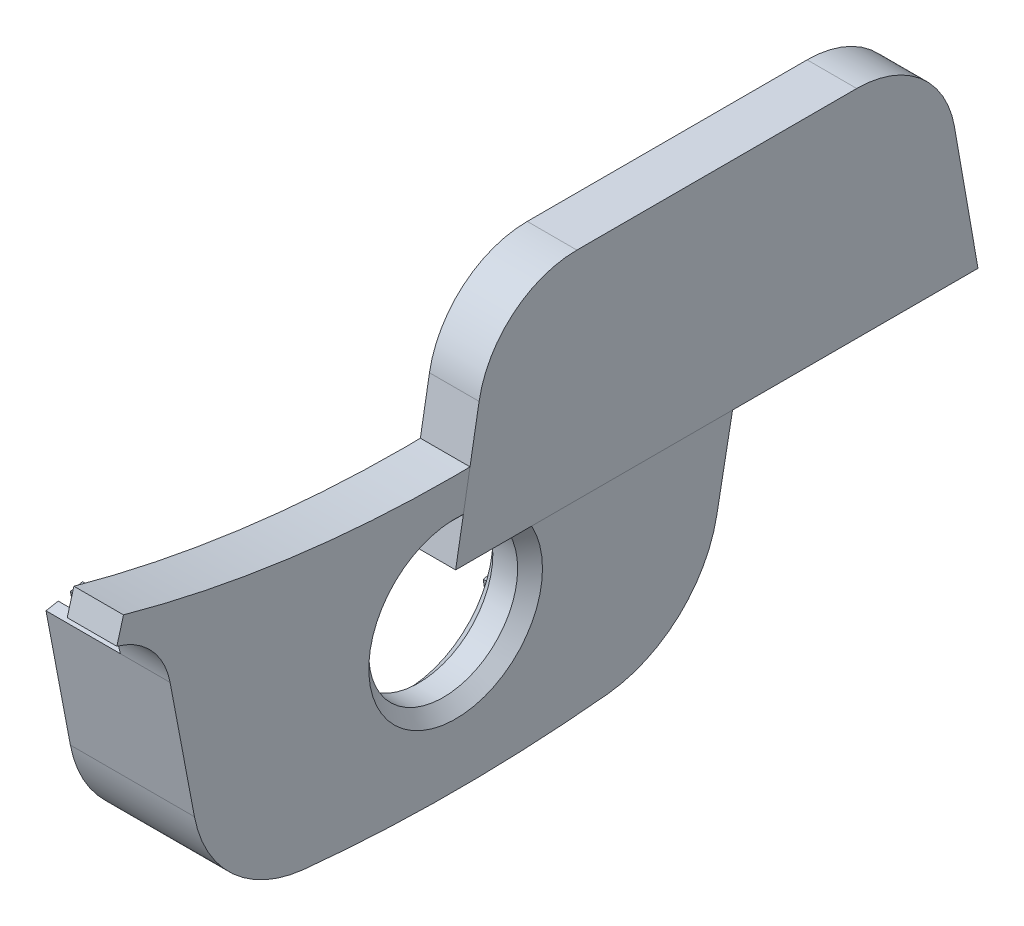
SolidWorks part; units mm, degrees
ref_plane "Спереди" through (0, 0, 0) normal (0, 0, 1) x (1, 0, 0)
ref_plane "Сверху" through (0, 0, 0) normal (0, 1, 0) x (1, 0, 0)
ref_plane "Справа" through (0, 0, 0) normal (1, 0, 0) x (0, 0, -1)
sketch "Эскиз2" plane through (0, 0, 0) normal (1, 0, 0) x (0, 0, -1)
  line L0 (0, 0) -> (21.05, 0)
  line L1 (0, 0) -> (0.946, 5.4091)
  line L2 (4.8862, 8.72) -> (16.1638, 8.72)
  line L3 (20.104, 5.4091) -> (21.05, 0)
  line L4 (10.525, 0) -> (10.525, 8.72) construction
  line L5 (-0.595, -0.5) -> (0.4534, 5.4952)
  line L6 (-0.595, -0.5) -> (21.645, -0.5)
  line L7 (20.5966, 5.4952) -> (21.645, -0.5)
  line L8 (4.8862, 9.22) -> (16.1638, 9.22)
  arc A0 (4.8862, 8.72) -> (0.946, 5.4091) centre (4.8862, 4.72) ccw
  arc A1 (16.1638, 8.72) -> (20.104, 5.4091) centre (16.1638, 4.72) cw
  arc A2 (4.8862, 9.22) -> (0.4534, 5.4952) centre (4.8862, 4.72) ccw
  arc A3 (16.1638, 9.22) -> (20.5966, 5.4952) centre (16.1638, 4.72) cw
  point P9 (1.525, 8.72)
  point P12 (19.525, 8.72)
  dimension "D4" = 4
  dimension "D1" = 21.05
  dimension "D2" = 18
  dimension "D3" = 8.72
  dimension "D5" = 0.5
extrude "Бобышка-Вытянуть1" add sketch "Эскиз2" along normal blind 2 contours A0 L1 L0 L3 A1 L2
sketch "Эскиз3" plane through (0, 0, 0) normal (1, 0, 0) x (0, 0, -1)
  line L2 (-18.1261, 6.7006) -> (18.1261, 6.7006) construction
  line L3 (11.5066, 1.8287) -> (10.5244, -3.3503)
  line L4 (-10.5244, -3.3503) -> (-11.5066, 1.8287)
  line L5 (-13.3834, 5.1238) -> (-13.6511, 4.1603)
  line L6 (13.3834, 5.1238) -> (13.6511, 4.1603)
  arc A0 (-13.3834, 5.1238) -> (13.3834, 5.1238) centre (0, 53.2994) ccw
  arc A6 (11.5066, 1.8287) -> (13.6511, 4.1603) centre (14.4541, 1.2698) cw
  arc A7 (10.5244, -3.3503) -> (6.1131, -7.3935) centre (5.612, -2.4187) cw
  arc A8 (-6.1131, -7.3935) -> (6.1131, -7.3935) centre (0, 53.2994) ccw
  arc A9 (-6.1131, -7.3935) -> (-10.5244, -3.3503) centre (-5.612, -2.4187) cw
  arc A10 (-11.5066, 1.8287) -> (-13.6511, 4.1603) centre (-14.4541, 1.2698) ccw
  point P14 (-18.1261, 6.7006)
  point P15 (18.1261, 6.7006)
  dimension "D3" = 100
extrude "Бобышка-Вытянуть2" add sketch "Эскиз3" along normal blind 2 separate body
sketch "Эскиз4" plane through (2, 0, 0) normal (1, 0, 0) x (0, 0, -1)
  line L1 (-11.0154, 1.9219) -> (-10.0332, -3.2572)
  line L2 (-10.5241, 2.0151) -> (-9.542, -3.164)
  line L4 (-13.3834, 5.1238) -> (-13.6511, 4.1603)
  line L5 (-13.3834, 5.1238) -> (-13.6511, 4.1603)
  line L8 (-11.5066, 1.8287) -> (-10.5244, -3.3503)
  line L9 (-10.0329, 2.1082) -> (-9.0507, -3.0708)
  line L10 (-11.5066, 1.8287) -> (-11.0154, 1.9219)
  line L12 (-6.1131, -5.8827) -> (-6.1847, -6.3775)
  line L13 (-6.2562, -6.8724) -> (-6.3278, -7.3672)
  line L14 (-11.5066, 1.8287) -> (-11.0154, 1.9219)
  line L15 (-10.5241, 2.0151) -> (-10.0329, 2.1082)
  line L16 (0, 0) -> (0, 8.4127) construction
  line L17 (-11.5066, 1.8287) -> (-10.5244, -3.3503)
  line L18 (-11.5066, 1.8287) -> (-10.5244, -3.3503)
  line L23 (10.5244, -3.3503) -> (11.5066, 1.8287)
  line L24 (10.5244, -3.3503) -> (11.5066, 1.8287)
  line L25 (13.6511, 4.1603) -> (13.3834, 5.1238)
  line L26 (13.6511, 4.1603) -> (13.3834, 5.1238)
  arc A0 (-9.0507, -3.0708) -> (-6.1131, -5.8827) centre (-5.612, -2.4187) ccw
  arc A1 (-11.5066, 1.8287) -> (-13.6511, 4.1603) centre (-14.4541, 1.2698) ccw
  arc A2 (-11.5066, 1.8287) -> (-13.6511, 4.1603) centre (-14.4541, 1.2698) ccw
  arc A3 (-10.0332, -3.2572) -> (-6.2562, -6.8724) centre (-5.612, -2.4187) ccw
  arc A4 (-10.5244, -3.3503) -> (-6.1131, -7.3935) centre (-5.612, -2.4187) ccw
  arc A5 (-9.542, -3.164) -> (-6.1847, -6.3775) centre (-5.612, -2.4187) ccw
  arc A7 (-13.3834, 5.1238) -> (13.3834, 5.1238) centre (0, 53.2994) ccw
  arc A8 (-10.5244, -3.3503) -> (-6.1131, -7.3935) centre (-5.612, -2.4187) ccw
  arc A9 (-10.5244, -3.3503) -> (-6.1131, -7.3935) centre (-5.612, -2.4187) ccw
  arc A13 (-13.3834, 5.1238) -> (13.3834, 5.1238) centre (0, 53.2994) ccw
  arc A18 (-6.1131, -7.3935) -> (6.1131, -7.3935) centre (0, 53.2994) ccw
  arc A19 (-6.1131, -7.3935) -> (6.1131, -7.3935) centre (0, 53.2994) ccw
  arc A20 (6.1131, -7.3935) -> (10.5244, -3.3503) centre (5.612, -2.4187) ccw
  arc A21 (-10.0332, -3.2572) -> (-6.063, -6.8961) centre (-5.612, -2.4187) ccw construction
  arc A22 (6.1131, -7.3935) -> (10.5244, -3.3503) centre (5.612, -2.4187) ccw
  arc A24 (13.6511, 4.1603) -> (11.5066, 1.8287) centre (14.4541, 1.2698) ccw
  arc A25 (13.6511, 4.1603) -> (11.5066, 1.8287) centre (14.4541, 1.2698) ccw
  line M63 (-11.5066, 1.8287) -> (-10.5244, -3.3503)
  arc M64 (-10.5244, -3.3503) -> (-6.1131, -7.3935) centre (-5.612, -2.4187) ccw
  dimension "D1" = 0
  dimension "D3" = 0.5
  dimension "D4" = 0.5
  dimension "D6" = 0.5
extrude "Бобышка-Вытянуть5" add sketch "Эскиз4" against normal blind 5 contours A3 L1 L10 L13 M63 M64 | L2 A5 L12 A0 L9 L15
mirror "Зеркальное отражение1" about plane through (0, 0, 0) normal (0, 0, 1) of "Бобышка-Вытянуть5"
sketch "Эскиз6" plane through (2, 0, 0) normal (1, 0, 0) x (0, 0, -1)
  line L1 (1.3137, -7.2067) -> (6.5137, -7.2067)
  line L2 (1.3137, -7.2067) -> (1.3137, 2.9933)
  line L3 (1.3137, 2.9933) -> (6.5137, 2.9933)
  line L4 (6.5137, -7.2067) -> (6.5137, 2.9933)
  line L5 (1.3137, -7.2067) -> (6.5137, 2.9933) construction
  line L6 (1.3137, 2.9933) -> (6.5137, -7.2067) construction
  line L8 (-2.4843, -10.8567) -> (-9.1843, -10.8567)
  line L9 (-2.4843, -10.8567) -> (-2.4843, 6.6433)
  line L10 (-2.4843, 6.6433) -> (-9.1843, 6.6433)
  line L11 (-9.1843, -10.8567) -> (-9.1843, 6.6433)
  line L12 (-2.4843, -10.8567) -> (-9.1843, 6.6433) construction
  line L13 (-2.4843, 6.6433) -> (-9.1843, -10.8567) construction
  point P0 (3.9137, -2.1067)
  point P6 (-5.8343, -2.1067)
  dimension "D1" = 5.2
  dimension "D2" = 10.2
  dimension "D3" = 6.7
  dimension "D4" = 17.5
sketch "Эскиз7" plane through (0, 0, 0) normal (-1, 0, 0) x (0, 0, 1)
  circle A0 centre (0, -1.7006) radius 3
  arc A2 (-13.3834, 5.1238) -> (13.3834, 5.1238) centre (0, 53.2994) ccw construction
  point P2 (0, 3.2994)
  dimension "D1" = 6
  dimension "D2" = 5
extrude "Вырез-Вытянуть1" cut sketch "Эскиз7" against normal blind 10
chamfer "Фаска3" distance 0.5 angle 45 2 edges at (2, -1.7006, -3) (0, -1.7006, 3)
